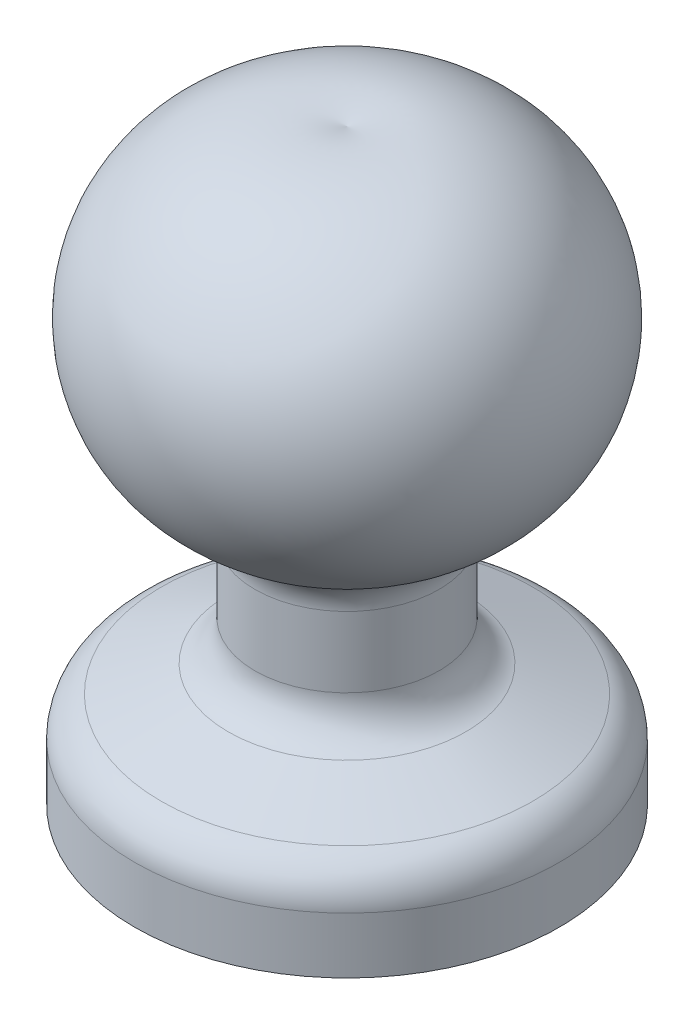
SolidWorks part; units mm, degrees
ref_plane "Front Plane" through (0, 0, 0) normal (0, 0, 1) x (1, 0, 0)
ref_plane "Top Plane" through (0, 0, 0) normal (0, 1, 0) x (1, 0, 0)
ref_plane "Right Plane" through (0, 0, 0) normal (1, 0, 0) x (0, 0, -1)
sketch "Sketch1" plane through (0, 0, 0) normal (0, 0, 1) x (1, 0, 0)
  line L0 (0, 86.0523) -> (0, -99.4928) construction
  line L1 (0, -68.0223) -> (25, -68.0223)
  line L2 (25, -68.0223) -> (25, -61.4111)
  line L3 (21.8523, -56.7669) -> (13.9776, -53.626)
  line L4 (10.83, -48.9818) -> (10.83, -40.688)
  line L5 (0, -68.0223) -> (0, 1.0908)
  arc A0 (13.5685, -36.2286) -> (0, 1.0908) centre (4.5228, -18.3911) ccw
  arc A1 (25, -61.4111) -> (21.8523, -56.7669) centre (20, -61.4111) ccw
  arc A2 (13.9776, -53.626) -> (10.83, -48.9818) centre (15.83, -48.9818) cw
  arc A3 (10.83, -40.688) -> (13.5685, -36.2286) centre (15.83, -40.688) cw
  point P12 (25, -58.0223)
  point P15 (10.83, -52.3706)
  point P18 (10.83, -37.3706)
  dimension "D1" = 20
  dimension "D4" = 5
  dimension "D2" = 15
  dimension "D3" = 10
  dimension "D5" = 25
revolve "Revolve3" add sketch "Sketch1" angle 360 about L0
